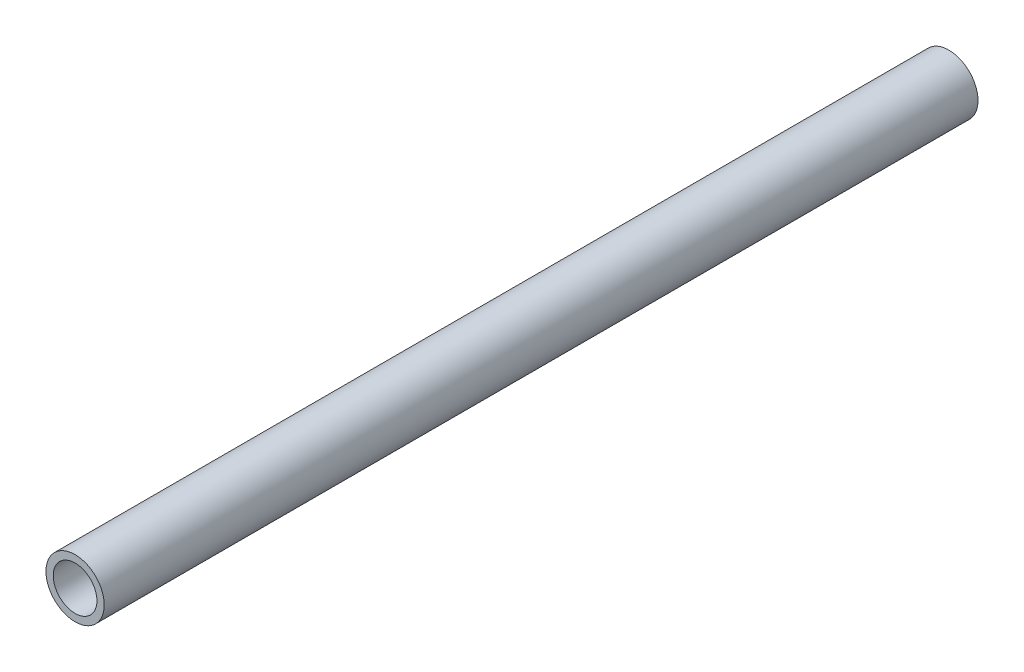
SolidWorks part; units mm, degrees
material "Thornel Mat VMA"
ref_plane "Ön Düzlem" through (0, 0, 0) normal (0, 0, 1) x (1, 0, 0)
ref_plane "Üst Düzlem" through (0, 0, 0) normal (0, 1, 0) x (1, 0, 0)
ref_plane "Sağ Düzlem" through (0, 0, 0) normal (1, 0, 0) x (0, 0, -1)
sketch "Çizim1" plane through (0, 0, 0) normal (0, 0, 1) x (1, 0, 0)
  circle A0 centre (0, 0) radius 8
  circle A1 centre (0, 0) radius 6
extrude "Yükseklik-Ekstrüzyon1" add sketch "Çizim1" along normal blind 240
